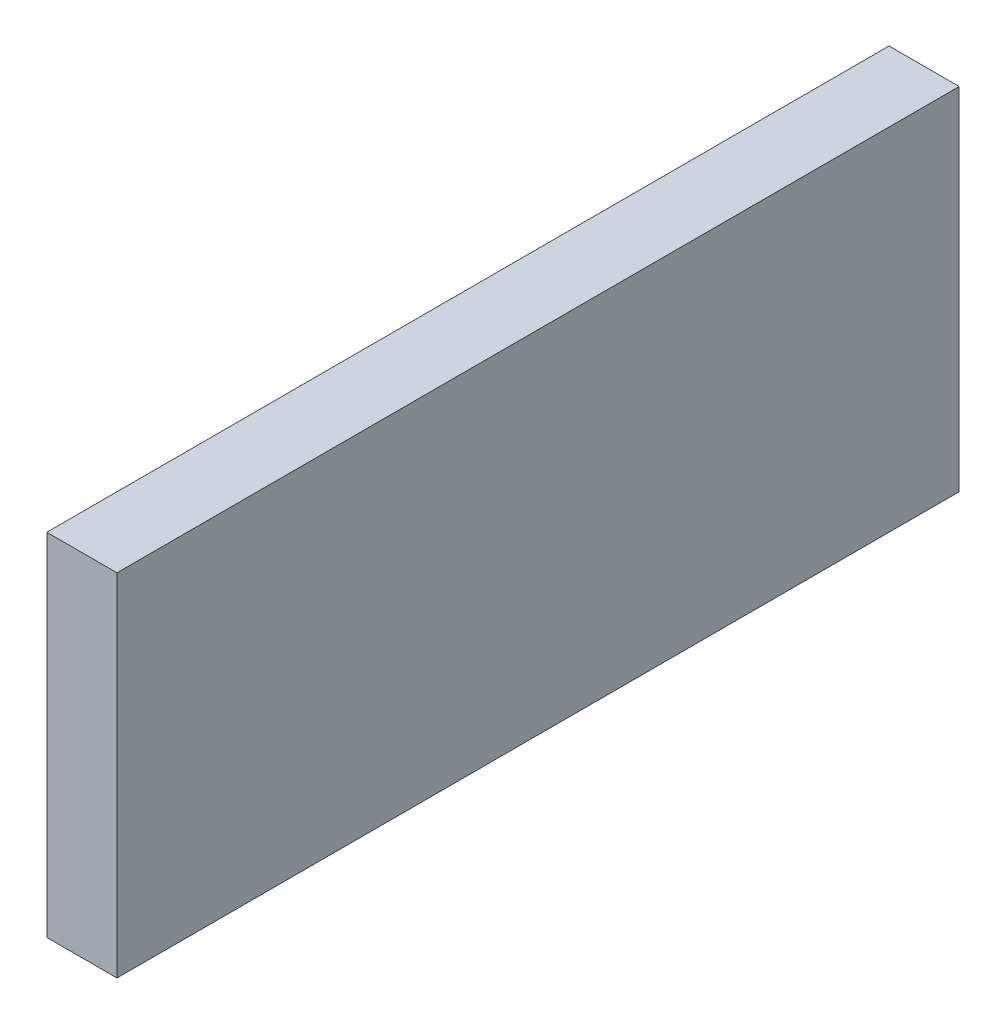
SolidWorks part; units mm, degrees
ref_plane "前视基准面" through (0, 0, 0) normal (0, 0, 1) x (1, 0, 0)
ref_plane "上视基准面" through (0, 0, 0) normal (0, 1, 0) x (1, 0, 0)
ref_plane "右视基准面" through (0, 0, 0) normal (1, 0, 0) x (0, 0, -1)
sketch "草图1" plane through (0, 0, 0) normal (0, 1, 0) x (1, 0, 0)
  line L1 (0, 0) -> (20, 0)
  line L2 (0, 0) -> (0, -240)
  line L3 (0, -240) -> (20, -240)
  line L4 (20, 0) -> (20, -240)
  dimension "D1" = 240
  dimension "D2" = 20
extrude "凸台-拉伸1" add sketch "草图1" along normal blind 100
